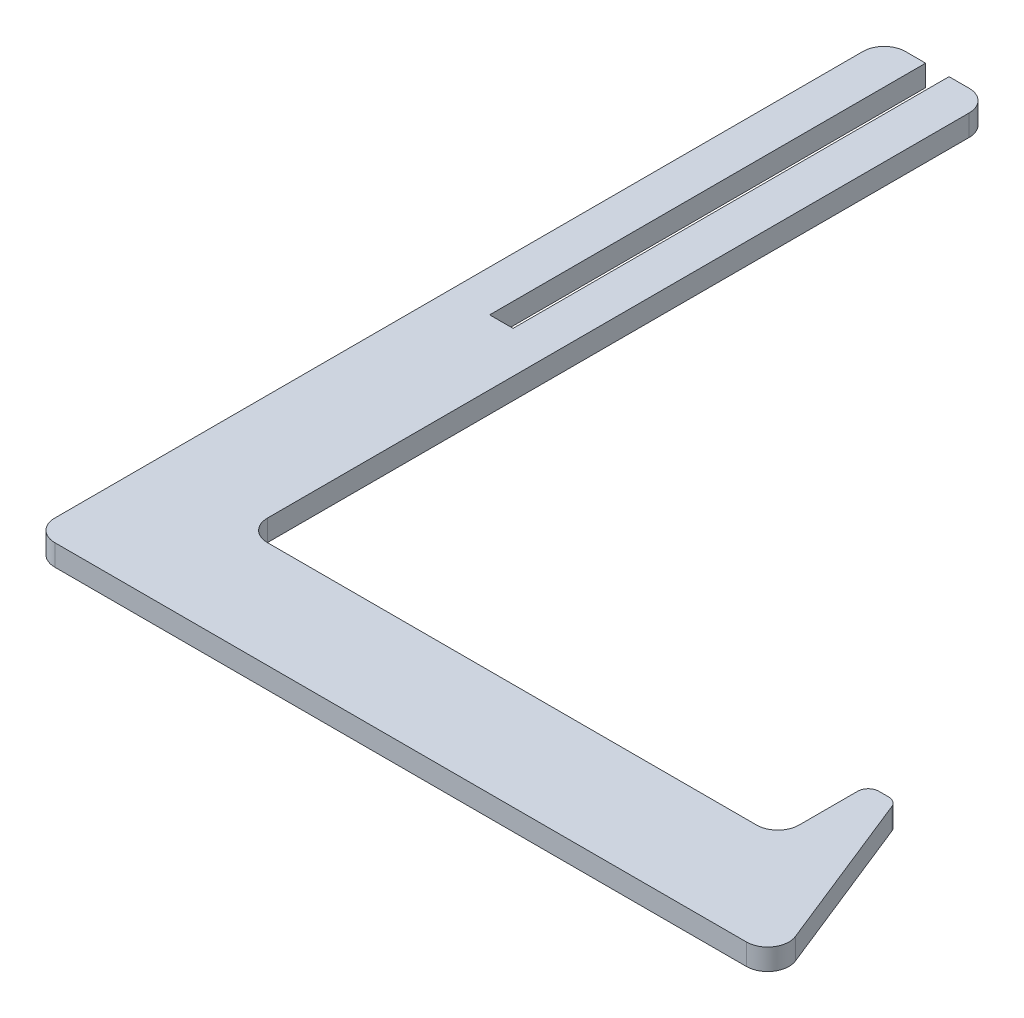
SolidWorks part; units mm, degrees
ref_plane "Front Plane" through (0, 0, 0) normal (0, 0, 1) x (1, 0, 0)
ref_plane "Top Plane" through (0, 0, 0) normal (0, 1, 0) x (1, 0, 0)
ref_plane "Right Plane" through (0, 0, 0) normal (1, 0, 0) x (0, 0, -1)
sketch "Sketch1" plane through (0, 0, 0) normal (0, 1, 0) x (1, 0, 0)
  line L0 (0, 0) -> (0, 80)
  line L1 (0, 80) -> (10, 80)
  line L2 (10, 80) -> (10, 10)
  line L3 (10, 10) -> (60, 10)
  line L4 (60, 10) -> (60, 25)
  line L5 (60, 25) -> (70, 0)
  line L6 (70, 0) -> (0, 0)
  dimension "D1" = 80
  dimension "D2" = 10
  dimension "D3" = 10
  dimension "D4" = 15
  dimension "D5" = 60
  dimension "D6" = 70
extrude "Boss-Extrude1" add sketch "Sketch1" along normal blind 2
fillet "Fillet1" radius 2 6 edges at (0, 1, 0) (70, 1, 0) (60, 1, -10) (10, 1, -10) (0, 1, -80) (10, 1, -80)
sketch "Sketch2" plane through (0, 2, 0) normal (0, 1, 0) x (1, 0, 0)
  line L0 (60, 18.5) -> (62.6, 18.5)
  line L1 (60, 25) -> (60, 12) construction
  line L2 (68.9029, 2.7428) -> (60, 25) construction
  line L3 (62.6, 18.5) -> (60, 25)
  line L4 (60, 25) -> (60, 18.5)
extrude "Cut-Extrude1" cut sketch "Sketch2" against normal through all
fillet "Fillet2" radius 1 2 edges at (62.6, 1, -18.5) (60, 1, -18.5)
sketch "Sketch3" plane through (0, 2, 0) normal (0, 1, 0) x (1, 0, 0)
  line L0 (8, 80) -> (2, 80) construction
  line L1 (3.9, 80) -> (6.1, 80)
  line L2 (3.9, 80) -> (3.9, 39)
  line L3 (3.9, 39) -> (6.1, 39)
  line L4 (6.1, 80) -> (6.1, 39)
  line L5 (0, 78) -> (0, 2) construction
  line L6 (10, 12) -> (10, 78) construction
  line L7 (2, 0) -> (67.0459, 0) construction
  dimension "D1" = 3.9
  dimension "D2" = 3.9
  dimension "D3" = 39
extrude "Cut-Extrude2" cut sketch "Sketch3" against normal blind 10
